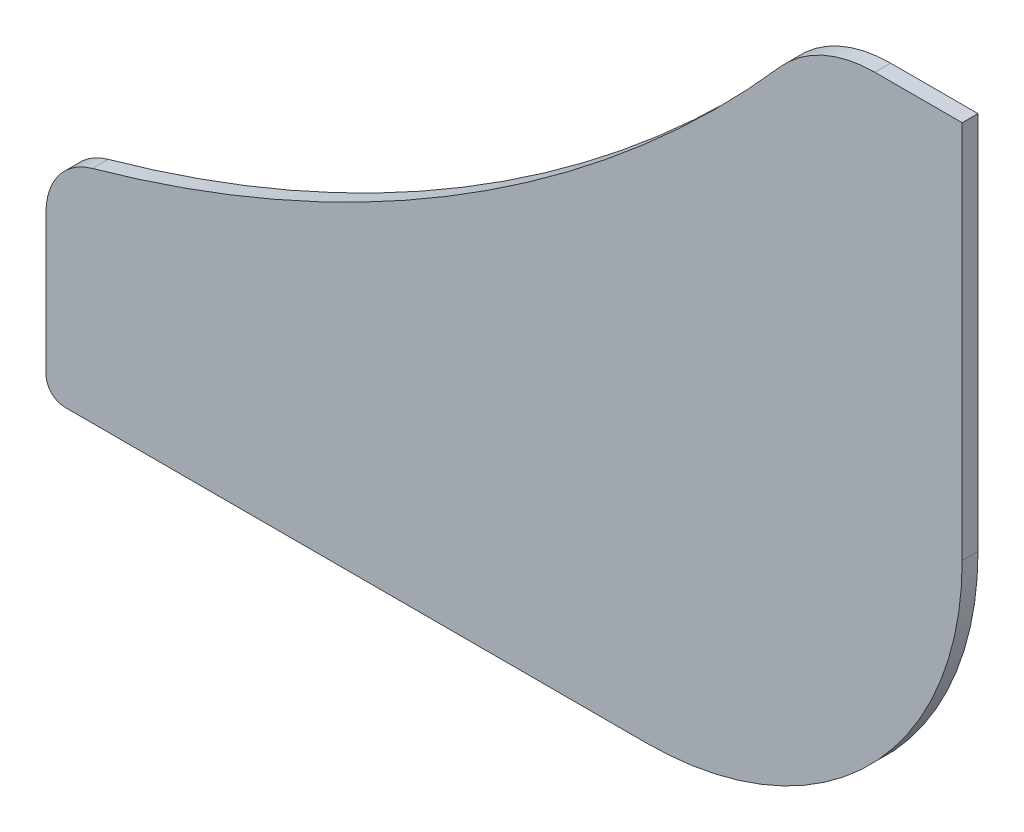
SolidWorks part; units mm, degrees
ref_plane "Front Plane" through (0, 0, 0) normal (0, 0, 1) x (1, 0, 0)
ref_plane "Top Plane" through (0, 0, 0) normal (0, 1, 0) x (1, 0, 0)
ref_plane "Right Plane" through (0, 0, 0) normal (1, 0, 0) x (0, 0, -1)
sketch "Sketch1" plane through (0, 0, 0) normal (0, 0, 1) x (1, 0, 0)
  line L15 (771.9038, 126.6023) -> (771.9038, 164.7023)
  line L17 (203.2, -203.2) -> (203.2, -279.4)
  line L20 (0, 0) -> (82.8917, 0) construction
  line L21 (0, 0) -> (0, -86.4487) construction
  line L22 (771.9038, 126.6023) -> (907.5478, 126.6023) construction
  line L25 (571.4712, -160.02) -> (571.4712, -7.62)
  line L26 (210.82, -287.02) -> (444.4712, -287.02)
  line L27 (312.4515, -206.6231) -> (466.4308, -117.7231) construction
  line L28 (451.8433, -111.2042) -> (546.0712, -26.0566) construction
  line L29 (571.4712, -7.62) -> (536.3464, -7.62)
  line L40 (361.6164, -231.6548) -> (133.988, -252.7091) construction
  line L41 (157.3315, -273.5734) -> (-70.4948, -254.7805) construction
  arc A5 (203.2, -279.4) -> (210.82, -287.02) centre (210.82, -279.4) ccw
  arc A6 (203.2, -203.2) -> (498.1985, -24.8733) centre (68.2384, 353.2267) ccw
  arc A7 (571.4712, -160.02) -> (444.4712, -287.02) centre (444.4712, -160.02) cw
  arc A8 (536.3464, -7.62) -> (498.1985, -24.8733) centre (536.3464, -58.42) ccw
  spline S0 degree 3 poles (360.3362, -232.1476) (361.944, -231.5594) (360.2733, -231.9279) (358.8705, -232.1286) (355.491, -232.7497) (351.3118, -233.4654) (345.8288, -234.3937) (339.3319, -235.4503) (331.8137, -236.6267) (323.3898, -237.8749) (314.1481, -239.1645) (304.196, -240.4529) (293.645, -241.7102) (282.6109, -242.9031) (271.2144, -244.0118) (259.5796, -245.0173) (247.8327, -245.923) (236.1052, -246.7089) (224.5878, -247.4466) (213.3874, -247.9449) (202.6055, -248.1613) (192.2857, -248.184) (182.5214, -248.0635) (173.413, -247.8762) (165.0492, -247.6957) (157.5243, -247.5827) (150.9198, -247.5968) (145.3176, -247.8045) (140.7752, -248.2212) (137.3462, -248.9332) (134.9534, -249.8477) (133.6053, -251.5229) (134.1931, -253.5982) (136.0729, -255.3852) (139.0627, -257.3468) (143.3055, -259.3644) (148.7486, -261.4241) (155.3647, -263.3995) (163.0752, -265.2124) (171.7927, -266.7481) (181.4066, -267.9166) (191.7956, -268.6246) (202.8233, -268.8006) (214.344, -268.4024) (226.142, -267.3648) (238.0677, -265.8064) (250.0128, -263.9526) (261.9011, -261.7778) (273.6057, -259.3395) (284.9982, -256.6886) (295.9553, -253.8811) (306.362, -250.9812) (316.1121, -248.0592) (325.1026, -245.1817) (333.2481, -242.4287) (340.4703, -239.8598) (346.6777, -237.559) (351.8912, -235.562) (355.8426, -233.9905) (359.046, -232.7314) (360.3362, -232.1476) (361.944, -231.5594) (360.2733, -231.9279) knots -0.012273 -0.005484 -0.001375 0 0.001366 0.005489 0.012269 0.02165 0.033497 0.04769 0.06403 0.082338 0.102396 0.123959 0.146791 0.170641 0.19524 0.220332 0.245646 0.27091 0.295825 0.31977 0.342911 0.365083 0.386049 0.405629 0.423597 0.43978 0.453966 0.466008 0.475784 0.483219 0.48846 0.492078 0.495706 0.500976 0.508553 0.518608 0.53108 0.545907 0.56292 0.581928 0.60273 0.625094 0.648778 0.673537 0.699099 0.724814 0.750772 0.776731 0.802428 0.827555 0.851851 0.875071 0.896936 0.917223 0.935694 0.952169 0.966419 0.978318 0.987727 0.994516 0.998625 1 1.001366 1.005489 1.012269 only from (347.4667, -231.1805) to (347.4667, -231.1805) construction
  spline S1 degree 3 poles (155.9851, -273.8364) (157.6707, -273.5362) (155.9614, -273.6091) (154.545, -273.5632) (151.109, -273.588) (146.869, -273.5671) (141.3082, -273.5292) (134.7264, -273.4415) (127.1182, -273.2946) (118.6055, -273.0609) (109.2803, -272.7261) (99.2556, -272.2668) (88.6466, -271.6729) (77.573, -270.9316) (66.1571, -270.0445) (54.5244, -269.0143) (42.7988, -267.8665) (31.1129, -266.6039) (19.6424, -265.3305) (8.5257, -263.8763) (-2.1301, -262.2171) (-12.2969, -260.4475) (-21.892, -258.6332) (-30.8295, -256.8671) (-39.0349, -255.237) (-46.4259, -253.8191) (-52.9324, -252.6861) (-58.4856, -251.9178) (-63.0313, -251.5394) (-66.5319, -251.6451) (-69.0472, -252.1302) (-70.6657, -253.5459) (-70.4472, -255.6917) (-68.9062, -257.778) (-66.3025, -260.229) (-62.4745, -262.9527) (-57.4718, -265.9263) (-51.2992, -269.0205) (-44.0206, -272.1448) (-35.7023, -275.171) (-26.4373, -277.9912) (-16.3291, -280.4924) (-5.4995, -282.5807) (5.9153, -284.1891) (17.7142, -285.2159) (29.7294, -285.7521) (41.8149, -286.0007) (53.9003, -285.9233) (65.8505, -285.5546) (77.5302, -284.9222) (88.8084, -284.06) (99.5605, -283.0113) (109.6699, -281.8268) (119.0235, -280.5542) (127.5233, -279.2575) (135.0819, -277.9817) (141.5945, -276.7938) (147.0755, -275.7324) (151.2398, -274.8709) (154.6131, -274.1873) (155.9851, -273.8364) (157.6707, -273.5362) (155.9614, -273.6091) knots -0.012273 -0.005484 -0.001375 0 0.001366 0.005489 0.012269 0.02165 0.033497 0.04769 0.06403 0.082338 0.102396 0.123959 0.146791 0.170641 0.19524 0.220332 0.245646 0.27091 0.295825 0.31977 0.342911 0.365083 0.386049 0.405629 0.423597 0.43978 0.453966 0.466008 0.475784 0.483219 0.48846 0.492078 0.495706 0.500976 0.508553 0.518608 0.53108 0.545907 0.56292 0.581928 0.60273 0.625094 0.648778 0.673537 0.699099 0.724814 0.750772 0.776731 0.802428 0.827555 0.851851 0.875071 0.896936 0.917223 0.935694 0.952169 0.966419 0.978318 0.987727 0.994516 0.998625 1 1.001366 1.005489 1.012269 only from (157.3315, -273.5734) to (157.3315, -273.5734) construction
  spline S3 degree 3 poles (360.3362, -232.1476) (361.944, -231.5594) (360.2733, -231.9279) (358.8705, -232.1286) (355.491, -232.7497) (351.3118, -233.4654) (345.8288, -234.3937) (339.3319, -235.4503) (331.8137, -236.6267) (323.3898, -237.8749) (314.1481, -239.1645) (304.196, -240.4529) (293.645, -241.7102) (282.6109, -242.9031) (271.2144, -244.0118) (259.5796, -245.0173) (247.8327, -245.923) (236.1052, -246.7089) (224.5878, -247.4466) (213.3874, -247.9449) (202.6055, -248.1613) (192.2857, -248.184) (182.5214, -248.0635) (173.413, -247.8762) (165.0492, -247.6957) (157.5243, -247.5827) (150.9198, -247.5968) (145.3176, -247.8045) (140.7752, -248.2212) (137.3462, -248.9332) (134.9534, -249.8477) (133.6053, -251.5229) (134.1931, -253.5982) (136.0729, -255.3852) (139.0627, -257.3468) (143.3055, -259.3644) (148.7486, -261.4241) (155.3647, -263.3995) (163.0752, -265.2124) (171.7927, -266.7481) (181.4066, -267.9166) (191.7956, -268.6246) (202.8233, -268.8006) (214.344, -268.4024) (226.142, -267.3648) (238.0677, -265.8064) (250.0128, -263.9526) (261.9011, -261.7778) (273.6057, -259.3395) (284.9982, -256.6886) (295.9553, -253.8811) (306.362, -250.9812) (316.1121, -248.0592) (325.1026, -245.1817) (333.2481, -242.4287) (340.4703, -239.8598) (346.6777, -237.559) (351.8912, -235.562) (355.8426, -233.9905) (359.046, -232.7314) (360.3362, -232.1476) (361.944, -231.5594) (360.2733, -231.9279) knots -0.012273 -0.005484 -0.001375 0 0.001366 0.005489 0.012269 0.02165 0.033497 0.04769 0.06403 0.082338 0.102396 0.123959 0.146791 0.170641 0.19524 0.220332 0.245646 0.27091 0.295825 0.31977 0.342911 0.365083 0.386049 0.405629 0.423597 0.43978 0.453966 0.466008 0.475784 0.483219 0.48846 0.492078 0.495706 0.500976 0.508553 0.518608 0.53108 0.545907 0.56292 0.581928 0.60273 0.625094 0.648778 0.673537 0.699099 0.724814 0.750772 0.776731 0.802428 0.827555 0.851851 0.875071 0.896936 0.917223 0.935694 0.952169 0.966419 0.978318 0.987727 0.994516 0.998625 1 1.001366 1.005489 1.012269 only from (361.6164, -231.6548) to (361.6164, -231.6548) construction
  spline S8 degree 3 poles (155.9851, -273.8364) (157.6707, -273.5362) (155.9614, -273.6091) (154.545, -273.5632) (151.109, -273.588) (146.869, -273.5671) (141.3082, -273.5292) (134.7264, -273.4415) (127.1182, -273.2946) (118.6055, -273.0609) (109.2803, -272.7261) (99.2556, -272.2668) (88.6466, -271.6729) (77.573, -270.9316) (66.1571, -270.0445) (54.5244, -269.0143) (42.7988, -267.8665) (31.1129, -266.6039) (19.6424, -265.3305) (8.5257, -263.8763) (-2.1301, -262.2171) (-12.2969, -260.4475) (-21.892, -258.6332) (-30.8295, -256.8671) (-39.0349, -255.237) (-46.4259, -253.8191) (-52.9324, -252.6861) (-58.4856, -251.9178) (-63.0313, -251.5394) (-66.5319, -251.6451) (-69.0472, -252.1302) (-70.6657, -253.5459) (-70.4472, -255.6917) (-68.9062, -257.778) (-66.3025, -260.229) (-62.4745, -262.9527) (-57.4718, -265.9263) (-51.2992, -269.0205) (-44.0206, -272.1448) (-35.7023, -275.171) (-26.4373, -277.9912) (-16.3291, -280.4924) (-5.4995, -282.5807) (5.9153, -284.1891) (17.7142, -285.2159) (29.7294, -285.7521) (41.8149, -286.0007) (53.9003, -285.9233) (65.8505, -285.5546) (77.5302, -284.9222) (88.8084, -284.06) (99.5605, -283.0113) (109.6699, -281.8268) (119.0235, -280.5542) (127.5233, -279.2575) (135.0819, -277.9817) (141.5945, -276.7938) (147.0755, -275.7324) (151.2398, -274.8709) (154.6131, -274.1873) (155.9851, -273.8364) (157.6707, -273.5362) (155.9614, -273.6091) knots -0.012273 -0.005484 -0.001375 0 0.001366 0.005489 0.012269 0.02165 0.033497 0.04769 0.06403 0.082338 0.102396 0.123959 0.146791 0.170641 0.19524 0.220332 0.245646 0.27091 0.295825 0.31977 0.342911 0.365083 0.386049 0.405629 0.423597 0.43978 0.453966 0.466008 0.475784 0.483219 0.48846 0.492078 0.495706 0.500976 0.508553 0.518608 0.53108 0.545907 0.56292 0.581928 0.60273 0.625094 0.648778 0.673537 0.699099 0.724814 0.750772 0.776731 0.802428 0.827555 0.851851 0.875071 0.896936 0.917223 0.935694 0.952169 0.966419 0.978318 0.987727 0.994516 0.998625 1 1.001366 1.005489 1.012269 only from (157.3315, -273.5734) to (157.3315, -273.5734) construction
  point P19 (571.4712, -287.02)
  point P39 (157.3315, -273.5734)
  dimension "D2" = 25.4
  dimension "D3" = 203.2
  dimension "D6" = 127
  dimension "D10" = 127
  dimension "D11" = 50.8
  dimension "D13" = 38.1
  dimension "D14" = 7.62
  dimension "D4" = 279.4
  dimension "D5" = 83.82
  dimension "D7" = 177.8
  dimension "D8" = 144.2667
  dimension "D9" = 203.2
extrude "Boss-Extrude1" add sketch "Sketch1" along normal blind 6.35
fillet "Fillet1" radius 25.4 1 edges at (203.2, -203.2, 3.175)
